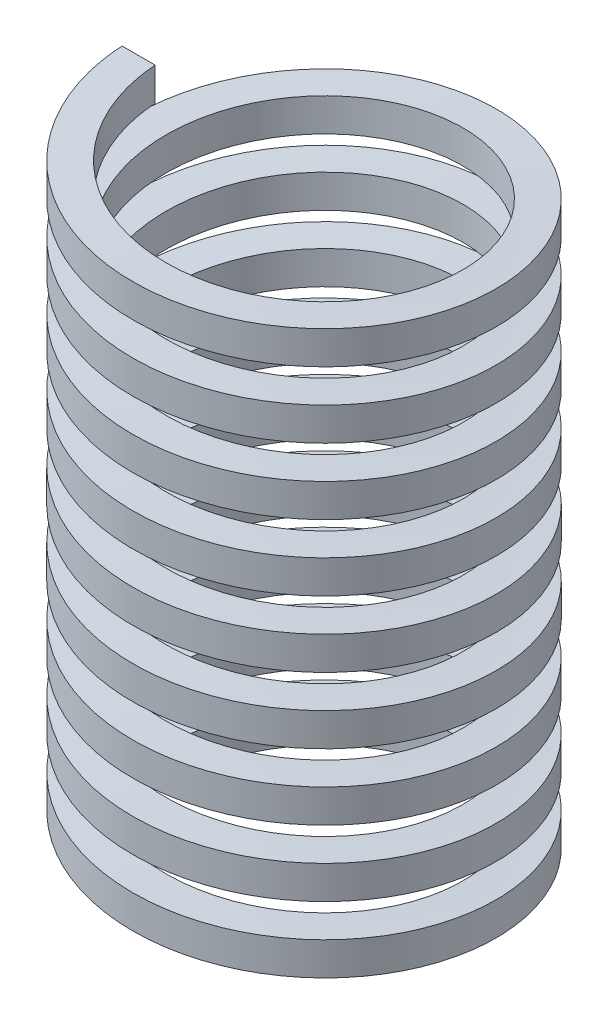
SolidWorks part; units mm, degrees
ref_plane "Front Plane" through (0, 0, 0) normal (0, 0, 1) x (1, 0, 0)
ref_plane "Top Plane" through (0, 0, 0) normal (0, 1, 0) x (1, 0, 0)
ref_plane "Right Plane" through (0, 0, 0) normal (1, 0, 0) x (0, 0, -1)
sketch "Sketch1" plane through (0, 0, 0) normal (0, 1, 0) x (1, 0, 0)
  circle A0 centre (0, 0) radius 50
curve "Helix/Spiral1" pitch 20 height 180 turns 9
sketch "Sketch2" plane through (0, 0, 0) normal (0, 0, 1) x (1, 0, 0)
  line L1 (-45, 5) -> (-55, 5)
  line L2 (-45, 5) -> (-45, -5)
  line L3 (-45, -5) -> (-55, -5)
  line L4 (-55, 5) -> (-55, -5)
  line L5 (-45, 5) -> (-55, -5) construction
  line L6 (-45, -5) -> (-55, 5) construction
  spline S0 degree 3 poles (-50, 0) (-50, 0.2124) (-49.3276, 0.6385) (-46.342, 1.2766) (-41.4993, 1.9149) (-34.9934, 2.5532) (-27.085, 3.1915) (-18.0912, 3.8298) (-8.3724, 4.4681) (1.682, 5.1064) (11.6689, 5.7447) (21.1883, 6.383) (29.8584, 7.0213) (37.332, 7.6596) (43.3094, 8.2979) (47.5511, 8.9362) (49.8871, 9.5745) (50.2238, 10.2128) (48.5477, 10.8511) (44.926, 11.4894) (39.5038, 12.1277) (32.4985, 12.766) (24.1907, 13.4043) (14.9134, 14.0426) (5.0384, 14.6809) (-5.0384, 15.3191) (-14.9134, 15.9574) (-24.1907, 16.5957) (-32.4985, 17.234) (-39.5038, 17.8723) (-44.926, 18.5106) (-48.5477, 19.1489) (-50.2238, 19.7872) (-49.8871, 20.4255) (-47.5511, 21.0638) (-43.3094, 21.7021) (-37.332, 22.3404) (-29.8584, 22.9787) (-21.1883, 23.617) (-11.6689, 24.2553) (-1.682, 24.8936) (8.3724, 25.5319) (18.0912, 26.1702) (27.085, 26.8085) (34.9934, 27.4468) (41.4993, 28.0851) (46.342, 28.7234) (49.3276, 29.3617) (50.3362, 30) (49.3276, 30.6383) (46.342, 31.2766) (41.4993, 31.9149) (34.9934, 32.5532) (27.085, 33.1915) (18.0912, 33.8298) (8.3724, 34.4681) (-1.682, 35.1064) (-11.6689, 35.7447) (-21.1883, 36.383) (-29.8584, 37.0213) (-37.332, 37.6596) (-43.3094, 38.2979) (-47.5511, 38.9362) (-49.8871, 39.5745) (-50.2238, 40.2128) (-48.5477, 40.8511) (-44.926, 41.4894) (-39.5038, 42.1277) (-32.4985, 42.766) (-24.1907, 43.4043) (-14.9134, 44.0426) (-5.0384, 44.6809) (5.0384, 45.3191) (14.9134, 45.9574) (24.1907, 46.5957) (32.4985, 47.234) (39.5038, 47.8723) (44.926, 48.5106) (48.5477, 49.1489) (50.2238, 49.7872) (49.8871, 50.4255) (47.5511, 51.0638) (43.3094, 51.7021) (37.332, 52.3404) (29.8584, 52.9787) (21.1883, 53.617) (11.6689, 54.2553) (1.682, 54.8936) (-8.3724, 55.5319) (-18.0912, 56.1702) (-27.085, 56.8085) (-34.9934, 57.4468) (-41.4993, 58.0851) (-46.342, 58.7234) (-49.3276, 59.3617) (-50.3362, 60) (-49.3276, 60.6383) (-46.342, 61.2766) (-41.4993, 61.9149) (-34.9934, 62.5532) (-27.085, 63.1915) (-18.0912, 63.8298) (-8.3724, 64.4681) (1.682, 65.1064) (11.6689, 65.7447) (21.1883, 66.383) (29.8584, 67.0213) (37.332, 67.6596) (43.3094, 68.2979) (47.5511, 68.9362) (49.8871, 69.5745) (50.2238, 70.2128) (48.5477, 70.8511) (44.926, 71.4894) (39.5038, 72.1277) (32.4985, 72.766) (24.1907, 73.4043) (14.9134, 74.0426) (5.0384, 74.6809) (-5.0384, 75.3191) (-14.9134, 75.9574) (-24.1907, 76.5957) (-32.4985, 77.234) (-39.5038, 77.8723) (-44.926, 78.5106) (-48.5477, 79.1489) (-50.2238, 79.7872) (-49.8871, 80.4255) (-47.5511, 81.0638) (-43.3094, 81.7021) (-37.332, 82.3404) (-29.8584, 82.9787) (-21.1883, 83.617) (-11.6689, 84.2553) (-1.682, 84.8936) (8.3724, 85.5319) (18.0912, 86.1702) (27.085, 86.8085) (34.9934, 87.4468) (41.4993, 88.0851) (46.342, 88.7234) (49.3276, 89.3617) (50.3362, 90) (49.3276, 90.6383) (46.342, 91.2766) (41.4993, 91.9149) (34.9934, 92.5532) (27.085, 93.1915) (18.0912, 93.8298) (8.3724, 94.4681) (-1.682, 95.1064) (-11.6689, 95.7447) (-21.1883, 96.383) (-29.8584, 97.0213) (-37.332, 97.6596) (-43.3094, 98.2979) (-47.5511, 98.9362) (-49.8871, 99.5745) (-50.2238, 100.2128) (-48.5477, 100.8511) (-44.926, 101.4894) (-39.5038, 102.1277) (-32.4985, 102.766) (-24.1907, 103.4043) (-14.9134, 104.0426) (-5.0384, 104.6809) (5.0384, 105.3191) (14.9134, 105.9574) (24.1907, 106.5957) (32.4985, 107.234) (39.5038, 107.8723) (44.926, 108.5106) (48.5477, 109.1489) (50.2238, 109.7872) (49.8871, 110.4255) (47.5511, 111.0638) (43.3094, 111.7021) (37.332, 112.3404) (29.8584, 112.9787) (21.1883, 113.617) (11.6689, 114.2553) (1.682, 114.8936) (-8.3724, 115.5319) (-18.0912, 116.1702) (-27.085, 116.8085) (-34.9934, 117.4468) (-41.4993, 118.0851) (-46.342, 118.7234) (-49.3276, 119.3617) (-50.3362, 120) (-49.3276, 120.6383) (-46.342, 121.2766) (-41.4993, 121.9149) (-34.9934, 122.5532) (-27.085, 123.1915) (-18.0912, 123.8298) (-8.3724, 124.4681) (1.682, 125.1064) (11.6689, 125.7447) (21.1883, 126.383) (29.8584, 127.0213) (37.332, 127.6596) (43.3094, 128.2979) (47.5511, 128.9362) (49.8871, 129.5745) (50.2238, 130.2128) (48.5477, 130.8511) (44.926, 131.4894) (39.5038, 132.1277) (32.4985, 132.766) (24.1907, 133.4043) (14.9134, 134.0426) (5.0384, 134.6809) (-5.0384, 135.3191) (-14.9134, 135.9574) (-24.1907, 136.5957) (-32.4985, 137.234) (-39.5038, 137.8723) (-44.926, 138.5106) (-48.5477, 139.1489) (-50.2238, 139.7872) (-49.8871, 140.4255) (-47.5511, 141.0638) (-43.3094, 141.7021) (-37.332, 142.3404) (-29.8584, 142.9787) (-21.1883, 143.617) (-11.6689, 144.2553) (-1.682, 144.8936) (8.3724, 145.5319) (18.0912, 146.1702) (27.085, 146.8085) (34.9934, 147.4468) (41.4993, 148.0851) (46.342, 148.7234) (49.3276, 149.3617) (50.3362, 150) (49.3276, 150.6383) (46.342, 151.2766) (41.4993, 151.9149) (34.9934, 152.5532) (27.085, 153.1915) (18.0912, 153.8298) (8.3724, 154.4681) (-1.682, 155.1064) (-11.6689, 155.7447) (-21.1883, 156.383) (-29.8584, 157.0213) (-37.332, 157.6596) (-43.3094, 158.2979) (-47.5511, 158.9362) (-49.8871, 159.5745) (-50.2238, 160.2128) (-48.5477, 160.8511) (-44.926, 161.4894) (-39.5038, 162.1277) (-32.4985, 162.766) (-24.1907, 163.4043) (-14.9134, 164.0426) (-5.0384, 164.6809) (5.0384, 165.3191) (14.9134, 165.9574) (24.1907, 166.5957) (32.4985, 167.234) (39.5038, 167.8723) (44.926, 168.5106) (48.5477, 169.1489) (50.2238, 169.7872) (49.8871, 170.4255) (47.5511, 171.0638) (43.3094, 171.7021) (37.332, 172.3404) (29.8584, 172.9787) (21.1883, 173.617) (11.6689, 174.2553) (1.682, 174.8936) (-8.3724, 175.5319) (-18.0912, 176.1702) (-27.085, 176.8085) (-34.9934, 177.4468) (-41.4993, 178.0851) (-46.342, 178.7234) (-49.3276, 179.3615) (-50, 179.7876) (-50, 180) knots 0 0 0 0 0.003546 0.007092 0.010638 0.014184 0.01773 0.021277 0.024823 0.028369 0.031915 0.035461 0.039007 0.042553 0.046099 0.049645 0.053191 0.056738 0.060284 0.06383 0.067376 0.070922 0.074468 0.078014 0.08156 0.085106 0.088652 0.092199 0.095745 0.099291 0.102837 0.106383 0.109929 0.113475 0.117021 0.120567 0.124113 0.12766 0.131206 0.134752 0.138298 0.141844 0.14539 0.148936 0.152482 0.156028 0.159574 0.163121 0.166667 0.170213 0.173759 0.177305 0.180851 0.184397 0.187943 0.191489 0.195035 0.198582 0.202128 0.205674 0.20922 0.212766 0.216312 0.219858 0.223404 0.22695 0.230496 0.234043 0.237589 0.241135 0.244681 0.248227 0.251773 0.255319 0.258865 0.262411 0.265957 0.269504 0.27305 0.276596 0.280142 0.283688 0.287234 0.29078 0.294326 0.297872 0.301418 0.304965 0.308511 0.312057 0.315603 0.319149 0.322695 0.326241 0.329787 0.333333 0.336879 0.340426 0.343972 0.347518 0.351064 0.35461 0.358156 0.361702 0.365248 0.368794 0.37234 0.375887 0.379433 0.382979 0.386525 0.390071 0.393617 0.397163 0.400709 0.404255 0.407801 0.411348 0.414894 0.41844 0.421986 0.425532 0.429078 0.432624 0.43617 0.439716 0.443262 0.446809 0.450355 0.453901 0.457447 0.460993 0.464539 0.468085 0.471631 0.475177 0.478723 0.48227 0.485816 0.489362 0.492908 0.496454 0.5 0.503546 0.507092 0.510638 0.514184 0.51773 0.521277 0.524823 0.528369 0.531915 0.535461 0.539007 0.542553 0.546099 0.549645 0.553191 0.556738 0.560284 0.56383 0.567376 0.570922 0.574468 0.578014 0.58156 0.585106 0.588652 0.592199 0.595745 0.599291 0.602837 0.606383 0.609929 0.613475 0.617021 0.620567 0.624113 0.62766 0.631206 0.634752 0.638298 0.641844 0.64539 0.648936 0.652482 0.656028 0.659574 0.663121 0.666667 0.670213 0.673759 0.677305 0.680851 0.684397 0.687943 0.691489 0.695035 0.698582 0.702128 0.705674 0.70922 0.712766 0.716312 0.719858 0.723404 0.72695 0.730496 0.734043 0.737589 0.741135 0.744681 0.748227 0.751773 0.755319 0.758865 0.762411 0.765957 0.769504 0.77305 0.776596 0.780142 0.783688 0.787234 0.79078 0.794326 0.797872 0.801418 0.804965 0.808511 0.812057 0.815603 0.819149 0.822695 0.826241 0.829787 0.833333 0.836879 0.840426 0.843972 0.847518 0.851064 0.85461 0.858156 0.861702 0.865248 0.868794 0.87234 0.875887 0.879433 0.882979 0.886525 0.890071 0.893617 0.897163 0.900709 0.904255 0.907801 0.911348 0.914894 0.91844 0.921986 0.925532 0.929078 0.932624 0.93617 0.939716 0.943262 0.946809 0.950355 0.953901 0.957447 0.960993 0.964539 0.968085 0.971631 0.975177 0.978723 0.98227 0.985816 0.989362 0.992908 0.996454 1 1 1 1 construction
  point P0 (-50, 0)
  dimension "D1" = 10
  dimension "D2" = 10
sweep "Sweep1" add profiles "Sketch2" path "Helix/Spiral1"
sketch "Sketch3" plane through (0, 0, 0) normal (1, 0, 0) x (0, 0, -1)
  line L0 (0, -5) -> (0, 185) construction
  dimension "D1" = 190
